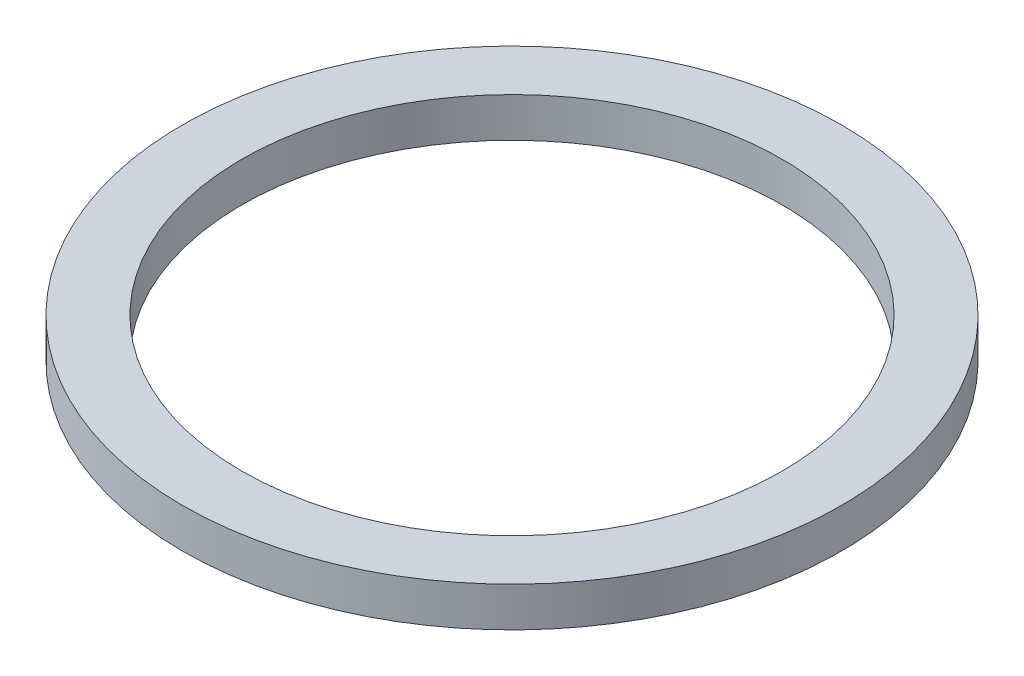
SolidWorks part; units mm, degrees
ref_plane "Front Plane" through (0, 0, 0) normal (0, 0, 1) x (1, 0, 0)
ref_plane "Top Plane" through (0, 0, 0) normal (0, 1, 0) x (1, 0, 0)
ref_plane "Right Plane" through (0, 0, 0) normal (1, 0, 0) x (0, 0, -1)
sketch "Sketch1" plane through (0, 0, 0) normal (0, 1, 0) x (1, 0, 0)
  circle A0 centre (0, 0) radius 8.325
  dimension "D1" = 16.65
extrude "Boss-Extrude1" add sketch "Sketch1" along normal blind 1
sketch "Sketch2" plane through (0, 1, 0) normal (0, 1, 0) x (1, 0, 0)
  circle A0 centre (0, 0) radius 6.825
  dimension "D1" = 13.65
extrude "Cut-Extrude1" cut sketch "Sketch2" against normal through all
